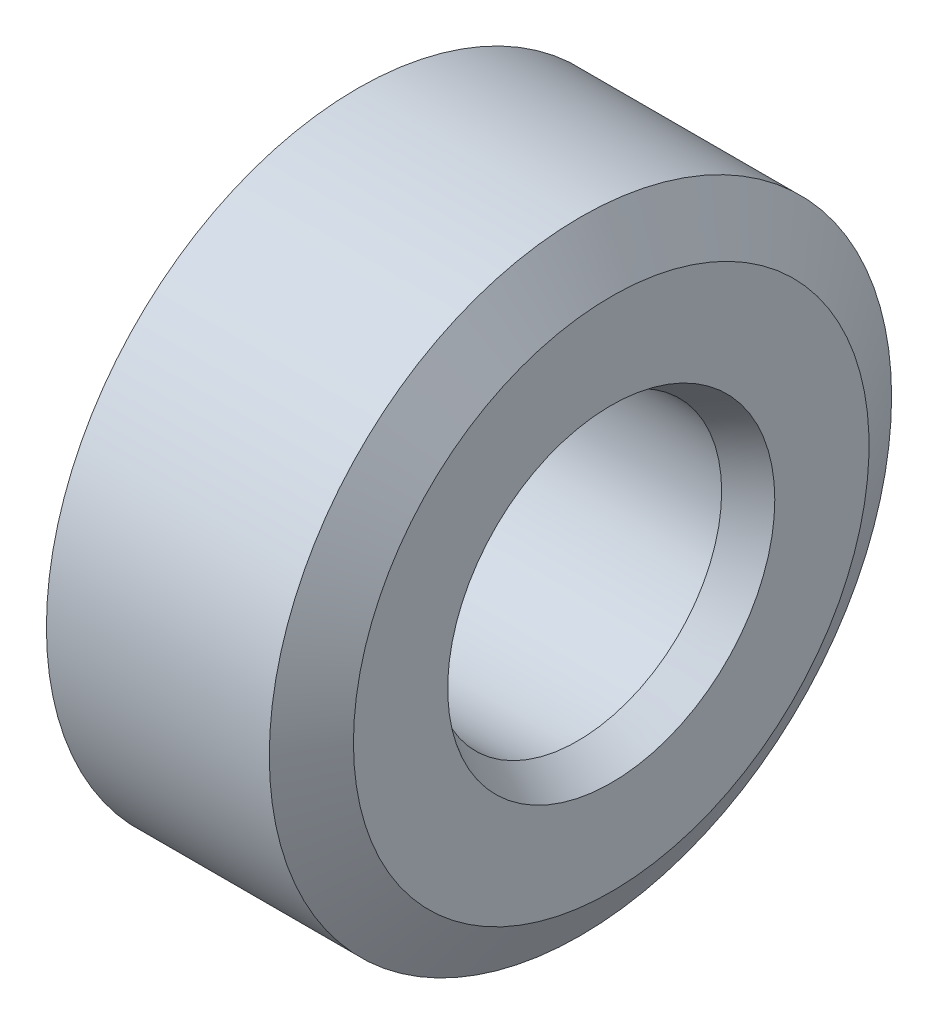
SolidWorks part; units mm, degrees
ref_plane "Ön Düzlem" through (0, 0, 0) normal (0, 0, 1) x (1, 0, 0)
ref_plane "Üst Düzlem" through (0, 0, 0) normal (0, 1, 0) x (1, 0, 0)
ref_plane "Sağ Düzlem" through (0, 0, 0) normal (1, 0, 0) x (0, 0, -1)
ref_plane "Plane1" through (0, 0, 0) normal (0, 0, -1) x (-1, 0, 0)
sketch "Sketch1" plane through (0, 0, 0) normal (0, 0, -1) x (-1, 0, 0)
  line L0 (-3.2, 2.9) -> (-3.2, 0)
  line L1 (-3.2, 0) -> (0, 0)
  line L2 (0, 0) -> (0, 2.9)
  line L3 (0, 2.9) -> (-1.6, 5.6713)
  line L4 (-1.6, 5.6713) -> (-3.2, 2.9)
  line L5 (-3.2, 0) -> (0, 0) construction
revolve "Revolve1" add sketch "Sketch1" angle 360 about L5
hole_wizard "M3 Clearance Hole1" positions "Sketch3" profile "Sketch2" hole size "M3" standard "ANSI Metric"
sketch "Sketch3" plane through (0, 0, 0) normal (-1, 0, 0) x (0, 0, 1)
  point P0 (0, 0)
sketch "Sketch2" plane through (0, 0, 0) normal (0, 1, 0) x (0, 0, 1)
  line L0 (0, 0) -> (0, 3.2)
  line L1 (0, 3.2) -> (1.621, 3.2)
  line L2 (1.621, 3.2) -> (1.621, 0)
  line L5 (1.621, 0) -> (0, 0)
  line L11 (0, -6.35) -> (0, 107.95) construction
  dimension "Thru Hole Dia." = 3.242
  dimension "Thru Hole Depth" = 3.2
chamfer "Chamfer1" distance 0.3789 angle 30 2 edges at (3.2, 0, 1.621) (0, 0, 1.621)
chamfer "Chamfer2" distance 2.5072 angle 60 1 edges at (1.6, 0, 5.6713)
